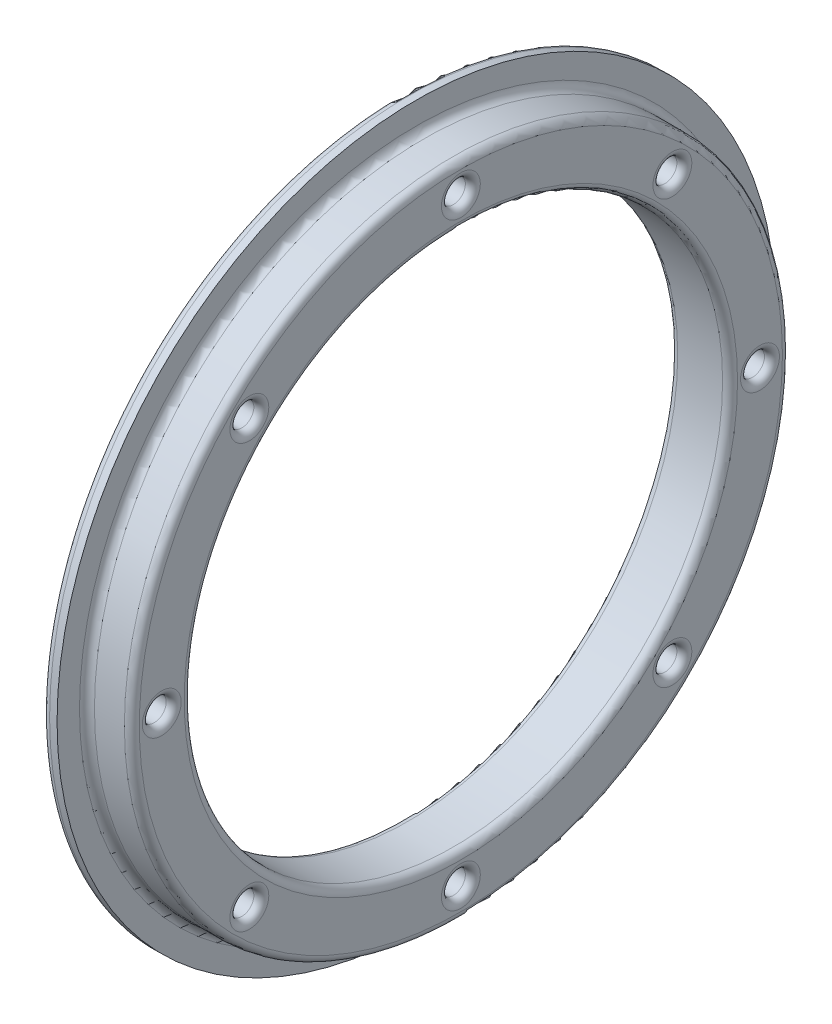
SolidWorks part; units mm, degrees
ref_plane "Front Plane" through (0, 0, 0) normal (0, 0, 1) x (1, 0, 0)
ref_plane "Top Plane" through (0, 0, 0) normal (0, 1, 0) x (1, 0, 0)
ref_plane "Right Plane" through (0, 0, 0) normal (1, 0, 0) x (0, 0, -1)
sketch "Sketch1" plane through (0, 0, 0) normal (1, 0, 0) x (0, 0, -1)
  line L0 (-34.925, 0) -> (-28.575, 0) construction
  circle A0 centre (0, 0) radius 34.925
  circle A1 centre (0, 0) radius 28.575
  circle A2 centre (-31.75, 0) radius 1.27
  circle A3 centre (-22.4506, 22.4506) radius 1.27
  circle A4 centre (0, 31.75) radius 1.27
  circle A5 centre (22.4506, 22.4506) radius 1.27
  circle A6 centre (31.75, 0) radius 1.27
  circle A7 centre (22.4506, -22.4506) radius 1.27
  circle A8 centre (0, -31.75) radius 1.27
  circle A9 centre (-22.4506, -22.4506) radius 1.27
  point P8 (-31.75, 0)
  point P25 (0, 0)
  dimension "D2" = 2.54
  dimension "D1" = 31.75
  dimension "D3" = 6.35
  dimension "D4" = 8
extrude "Boss-Extrude1" add sketch "Sketch1" along normal mid plane 6.35
sketch "Sketch2" plane through (-3.175, 0, 0) normal (-1, 0, 0) x (0, 0, 1)
  circle A0 centre (0, 0) radius 38.1
  circle A1 centre (0, 0) radius 34.925 construction
  circle A2 centre (0, 0) radius 34.925
  dimension "D1" = 76.2
extrude "Boss-Extrude2" add sketch "Sketch2" against normal blind 1.5875
fillet "Fillet1" radius 0.7937 21 edges at (-3.175, -22.4506, 21.1806) (-3.175, -31.75, -1.27) (-3.175, -22.4506, -23.7206) (-3.175, 0, -33.02) (-3.175, 22.4506, -23.7206) (-3.175, 31.75, -1.27) (-3.175, 22.4506, 21.1806) (-3.175, 0, 30.48) (-3.175, 0, -28.575) (3.175, -22.4506, 21.1806) (3.175, -22.4506, -23.7206) (3.175, 22.4506, -23.7206) (3.175, 22.4506, 21.1806) (3.175, 0, -28.575) (3.175, 0, -34.925) (3.175, 0, 30.48) (3.175, 31.75, -1.27) (3.175, 0, -33.02) (3.175, -31.75, -1.27) (-3.175, 0, 38.1) (-1.5875, 0, 34.925)
